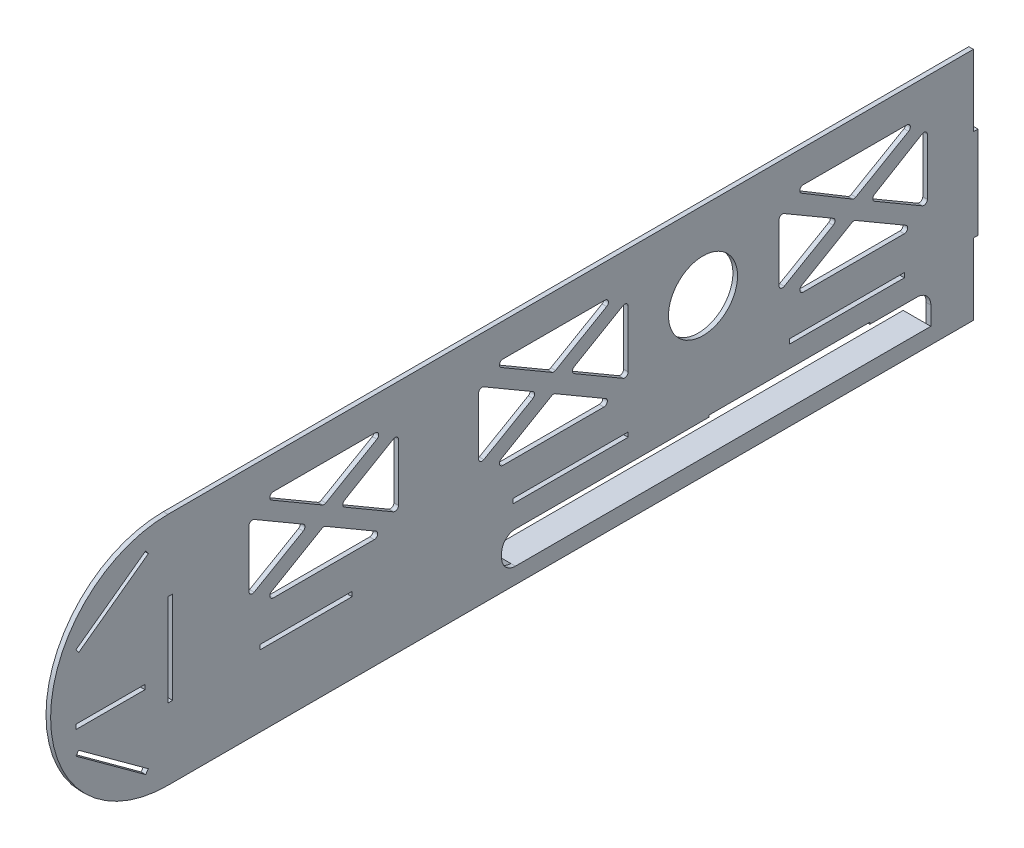
SolidWorks part; units mm, degrees
ref_plane "前视基准面" through (0, 0, 0) normal (0, 0, 1) x (1, 0, 0)
ref_plane "上视基准面" through (0, 0, 0) normal (0, 1, 0) x (1, 0, 0)
ref_plane "右视基准面" through (0, 0, 0) normal (1, 0, 0) x (0, 0, -1)
sketch "草图1" plane through (0, 0, 0) normal (1, 0, 0) x (0, 0, -1)
  line L0 (145, -36) -> (145, -38)
  line L1 (0, 51) -> (139, 51)
  line L2 (0, 51) -> (0, -51)
  line L3 (0, -51) -> (350, -51)
  line L4 (350, 51) -> (350, -51)
  line L5 (145, 51) -> (331.5, 51)
  line L6 (151, -44) -> (325.5, -44)
  line L7 (331.5, -36) -> (331.5, -39)
  line L8 (337.5, 51) -> (350, 51)
  line L10 (-40, -10) -> (-10, -10)
  line L11 (-40, -10) -> (-40, -8)
  line L12 (-40, -8) -> (-10, -8)
  line L13 (-10, -10) -> (-10, -8)
  line L49 (-40, 20) -> (-9.6982, 42.0918)
  line L50 (-40, 20) -> (-38.8218, 18.3839)
  line L51 (-9.6982, 42.0918) -> (-8.5199, 40.4757)
  line L52 (-38.8218, 18.3839) -> (-8.5199, 40.4757)
  line L53 (-51, 0) -> (0, 0)
  line L54 (-38.8218, -18.3839) -> (-8.5199, -40.4757)
  line L55 (-9.6982, -42.0918) -> (-8.5199, -40.4757)
  line L56 (-40, -20) -> (-38.8218, -18.3839)
  line L57 (-40, -20) -> (-9.6982, -42.0918)
  line L70 (350, 20) -> (352, 20)
  line L71 (350, 20) -> (350, -20)
  line L72 (352, 20) -> (352, -20)
  line L73 (350, -20) -> (352, -20)
  line L74 (0, 20) -> (0, -20)
  line L75 (0, 20) -> (2, 20)
  line L76 (0, -20) -> (2, -20)
  line L77 (2, 20) -> (2, -20)
  line L78 (139, 51) -> (145, 51)
  line L79 (331.5, 51) -> (337.5, 51)
  line L80 (151, -30) -> (325.5, -30)
  line L81 (151, -44) -> (151, -30)
  line L82 (331.5, -39) -> (331.5, -44)
  line L85 (325.5, -44) -> (331.5, -44)
  line L87 (235, -30) -> (305, -30)
  line L88 (235, -30) -> (235, -29.2)
  line L89 (235, -29.2) -> (305, -29.2)
  line L90 (305, -30) -> (305, -29.2)
  line L91 (145.5484, 36.6595) -> (189.8851, 36.6595)
  line L92 (135, 29.0479) -> (135, 4.2608)
  line L93 (145.5484, -3.3405) -> (189.4516, -3.3405)
  line L94 (200, 29.3884) -> (200, 4.6116)
  line L95 (176.5069, 15.7043) -> (197.7442, 3.3159)
  line L96 (158.585, 17.9016) -> (137.2558, 30.3436)
  line L97 (137.2514, 2.9626) -> (158.5806, 15.3077)
  line L98 (176.5069, 18.2957) -> (197.7442, 30.6841)
  line L99 (144.7926, 33.8638) -> (166.8743, 20.9828)
  line L100 (190.6365, 33.8613) -> (168.3815, 20.9803)
  line L101 (168.2558, 12.2603) -> (190.2074, -0.5448)
  line L102 (144.7926, -0.5448) -> (166.7442, 12.2603)
  line L103 (276.0709, 37) -> (321.089, 37)
  line L104 (265.5225, 28.9941) -> (265.5225, 4.207)
  line L105 (276.0709, -3.3943) -> (319.9742, -3.3943)
  line L106 (330, 28.9941) -> (330, 4.522)
  line L107 (307.0294, 15.31) -> (327.7442, 3.2264)
  line L108 (289.1076, 17.8477) -> (267.7784, 30.2898)
  line L109 (267.7739, 2.9088) -> (289.1032, 15.2538)
  line L110 (307.0153, 17.893) -> (327.7301, 30.2815)
  line L111 (275.2981, 34.2144) -> (297.3797, 20.9391)
  line L112 (321.8404, 34.2018) -> (298.904, 20.9265)
  line L113 (298.7784, 12.2065) -> (320.73, -0.5987)
  line L114 (275.3151, -0.5987) -> (297.2667, 12.2065)
  line L115 (40, -18) -> (80, -18)
  line L116 (40, -18) -> (40, -20)
  line L117 (80, -18) -> (80, -20)
  line L118 (40, -20) -> (80, -20)
  line L119 (150, -18) -> (200, -18)
  line L120 (150, -18) -> (150, -20)
  line L121 (200, -18) -> (200, -20)
  line L122 (150, -20) -> (200, -20)
  line L123 (270, -18) -> (320, -18)
  line L124 (270, -18) -> (270, -20)
  line L125 (320, -18) -> (320, -20)
  line L126 (270, -20) -> (320, -20)
  line L127 (45.7401, 36.6595) -> (90.0769, 36.6595)
  line L128 (35.1917, 29.0479) -> (35.1917, 4.2608)
  line L129 (45.7401, -3.3405) -> (89.6434, -3.3405)
  line L130 (100.1917, 29.0479) -> (100.1917, 4.271)
  line L131 (76.6986, 15.3638) -> (97.9359, 2.9754)
  line L132 (58.7768, 17.9016) -> (37.4476, 30.3436)
  line L133 (37.4431, 2.9626) -> (58.7724, 15.3077)
  line L134 (76.6986, 17.9552) -> (97.9359, 30.3436)
  line L135 (44.9843, 33.8638) -> (67.066, 20.9828)
  line L136 (90.8283, 33.8613) -> (68.5732, 20.9803)
  line L137 (68.4476, 12.2603) -> (90.3992, -0.5448)
  line L138 (44.9843, -0.5448) -> (66.9359, 12.2603)
  arc A0 (0, 51) -> (0, -51) centre (0, 0) ccw
  arc A3 (151, -44) -> (145, -38) centre (151, -38) cw
  arc A44 (331.5, -36) -> (325.5, -30) centre (325.5, -36) ccw
  arc A45 (151, -30) -> (145, -36) centre (151, -36) ccw
  arc A46 (97.9359, 30.3436) -> (100.1917, 29.0479) centre (98.6917, 29.0479) cw
  arc A47 (100.1917, 4.271) -> (97.9359, 2.9754) centre (98.6917, 4.271) cw
  arc A48 (197.7442, 30.6841) -> (200, 29.3884) centre (198.5, 29.3884) cw
  arc A49 (200, 4.6116) -> (197.7442, 3.3159) centre (198.5, 4.6116) cw
  arc A50 (176.5069, 15.7043) -> (176.5069, 18.2957) centre (177.2627, 17) cw
  arc A51 (158.585, 17.9016) -> (158.5806, 15.3077) centre (157.8292, 16.6059) cw
  arc A52 (137.2514, 2.9626) -> (135, 4.2608) centre (136.5, 4.2608) cw
  arc A53 (135, 29.0479) -> (137.2558, 30.3436) centre (136.5, 29.0479) cw
  arc A54 (144.7926, -0.5448) -> (145.5484, -3.3405) centre (145.5484, -1.8405) ccw
  arc A55 (189.4516, -3.3405) -> (190.2074, -0.5448) centre (189.4516, -1.8405) ccw
  arc A56 (168.2558, 12.2603) -> (166.7442, 12.2603) centre (167.5, 10.9646) ccw
  arc A57 (144.7926, 33.8638) -> (145.5484, 36.6595) centre (145.5484, 35.1595) cw
  arc A58 (189.8851, 36.6595) -> (190.6365, 33.8613) centre (189.8851, 35.1595) cw
  arc A59 (168.3815, 20.9803) -> (166.8743, 20.9828) centre (167.6301, 22.2785) cw
  arc A60 (327.7301, 30.2815) -> (330, 28.9941) centre (328.5, 28.9941) cw
  arc A61 (330, 4.522) -> (327.7442, 3.2264) centre (328.5, 4.522) cw
  arc A62 (307.0294, 15.31) -> (307.0153, 17.893) centre (307.7852, 16.6057) cw
  arc A63 (289.1076, 17.8477) -> (289.1032, 15.2538) centre (288.3518, 16.5521) cw
  arc A64 (267.7739, 2.9088) -> (265.5225, 4.207) centre (267.0225, 4.207) cw
  arc A65 (265.5225, 28.9941) -> (267.7784, 30.2898) centre (267.0225, 28.9941) cw
  arc A66 (275.3151, -0.5987) -> (276.0709, -3.3943) centre (276.0709, -1.8943) ccw
  arc A67 (319.9742, -3.3943) -> (320.73, -0.5987) centre (319.9742, -1.8943) ccw
  arc A68 (298.7784, 12.2065) -> (297.2667, 12.2065) centre (298.0225, 10.9108) ccw
  arc A69 (275.2981, 34.2144) -> (276.0709, 37) centre (276.0709, 35.5) cw
  arc A70 (321.089, 37) -> (321.8404, 34.2018) centre (321.089, 35.5) cw
  arc A71 (298.904, 20.9265) -> (297.3797, 20.9391) centre (298.1526, 22.2247) cw
  circle A72 centre (232.5, 17) radius 15
  arc A73 (76.6986, 15.3638) -> (76.6986, 17.9552) centre (77.4544, 16.6595) cw
  arc A74 (58.7768, 17.9016) -> (58.7724, 15.3077) centre (58.021, 16.6059) cw
  arc A75 (37.4431, 2.9626) -> (35.1917, 4.2608) centre (36.6917, 4.2608) cw
  arc A76 (35.1917, 29.0479) -> (37.4476, 30.3436) centre (36.6917, 29.0479) cw
  arc A77 (44.9843, -0.5448) -> (45.7401, -3.3405) centre (45.7401, -1.8405) ccw
  arc A78 (89.6434, -3.3405) -> (90.3992, -0.5448) centre (89.6434, -1.8405) ccw
  arc A79 (68.4476, 12.2603) -> (66.9359, 12.2603) centre (67.6917, 10.9646) ccw
  arc A80 (44.9843, 33.8638) -> (45.7401, 36.6595) centre (45.7401, 35.1595) cw
  arc A81 (90.0769, 36.6595) -> (90.8283, 33.8613) centre (90.0769, 35.1595) cw
  arc A82 (68.5732, 20.9803) -> (67.066, 20.9828) centre (67.8218, 22.2785) cw
  point P5 (40.1917, 36.6595)
  point P7 (331.5, -44)
  point P8 (286.5, 50)
  point P21 (145, -44)
  point P24 (95.6629, 36.6595)
  point P28 (40.1917, -3.3405)
  point P29 (95.1917, -3.3405)
  point P30 (40.1917, -3.3405)
  point P31 (35.1917, 1.6595)
  point P32 (150, -45)
  point P33 (100.1917, 1.6595)
  point P34 (100.1917, 31.6595)
  point P35 (35.1917, 31.6595)
  point P53 (140, 36.6595)
  point P58 (195.4712, 36.6595)
  point P59 (140, -3.3405)
  point P60 (195, -3.3405)
  point P61 (140, -3.3405)
  point P62 (135, 1.6595)
  point P63 (200, 2)
  point P64 (200, 32)
  point P65 (135, 31.6595)
  point P113 (270.5225, 37)
  point P118 (325.9937, 37)
  point P119 (270.5225, -3.3943)
  point P120 (325.5225, -3.3943)
  point P121 (270.5225, -3.3943)
  point P122 (265.5225, 1.6057)
  point P123 (330, 1.6057)
  point P124 (330, 31.6057)
  point P125 (265.5225, 31.6057)
  point P169 (350, -20)
  point P182 (-9.6982, -42.0918)
  point P184 (-40, -20)
  point P189 (352, 20)
  point P190 (352, -20)
  point P198 (350, 20)
  dimension "D1" = 1.5
  dimension "D2" = 1.5
  dimension "D3" = 1.5
  dimension "D5" = 1.5
  dimension "D6" = 1.5
  dimension "D7" = 1.5
  dimension "D8" = 1.5
  dimension "D9" = 1.5
  dimension "D10" = 1.5
  dimension "D11" = 1.5
  dimension "D12" = 1.5
  dimension "D13" = 1.5
  dimension "D14" = 1.5
  dimension "D15" = 1.5
  dimension "D16" = 1.5
  dimension "D17" = 1.5
  dimension "D18" = 1.5
  dimension "D19" = 1.5
  dimension "D20" = 1.5
  dimension "D21" = 1.5
  dimension "D22" = 1.5
  dimension "D23" = 1.5
  dimension "D24" = 1.5
  dimension "D25" = 1.5
  dimension "D26" = 1.5
  dimension "D27" = 1.5
  dimension "D28" = 1.5
  dimension "D29" = 1.5
  dimension "D30" = 1.5
  dimension "D31" = 1.5
  dimension "D32" = 1.5
  dimension "D33" = 1.5
  dimension "D34" = 1.5
  dimension "D35" = 1.5
  dimension "D36" = 1.5
  dimension "D37" = 1.5
  dimension "D41" = 2
  dimension "D42" = 37.5
  dimension "D43" = 2
extrude "凸台-拉伸3" add sketch "草图1" along normal blind 2
sketch "草图2" plane through (2, 0, 0) normal (1, 0, 0) x (0, 0, -1)
  line L0 (151, -44) -> (151, -51)
  line L1 (0, -51) -> (350, -51) construction
  line L2 (151, -44) -> (331.5, -44)
  line L3 (331.5, -44) -> (331.5, -51)
  line L4 (331.5, -51) -> (151, -51)
  line L5 (151, -30) -> (235, -30)
  line L6 (235, -30) -> (235, -29.2)
  line L7 (235, -29.2) -> (305, -29.2)
  line L8 (305, -29.2) -> (305, -30)
  line L9 (305, -30) -> (325.5, -30)
  line L10 (325.5, -30) -> (325.5, -25)
  line L11 (325.5, -25) -> (151, -25)
  line L12 (151, -25) -> (151, -30)
  arc A0 (151, -30) -> (145, -36) centre (151, -36) ccw construction
extrude "凸台-拉伸4" add sketch "草图2" against normal blind 12
